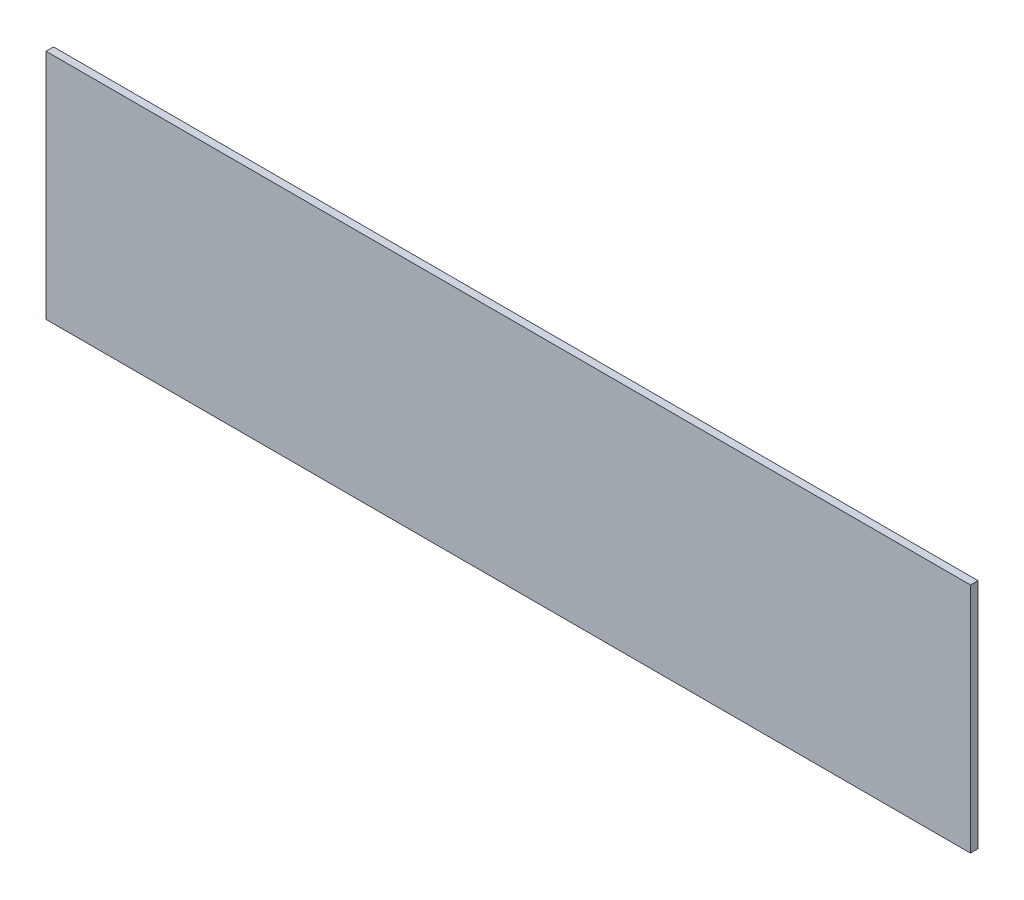
SolidWorks part; units mm, degrees
ref_plane "Front Plane" through (0, 0, 0) normal (0, 0, 1) x (1, 0, 0)
ref_plane "Top Plane" through (0, 0, 0) normal (0, 1, 0) x (1, 0, 0)
ref_plane "Right Plane" through (0, 0, 0) normal (1, 0, 0) x (0, 0, -1)
sketch "Sketch1" plane through (0, 0, 0) normal (0, 0, 1) x (1, 0, 0)
  line L0 (1230, 309) -> (1230, 0)
  line L1 (1230, 309) -> (0, 309)
  line L2 (1230, 0) -> (0, 0)
  line L3 (0, 309) -> (0, 0)
other "Pen Sketch1" parameters "D1"=69.7562, "D2"=44.2015
extrude "Boss-Extrude1" add sketch "Sketch1" along normal blind 10
